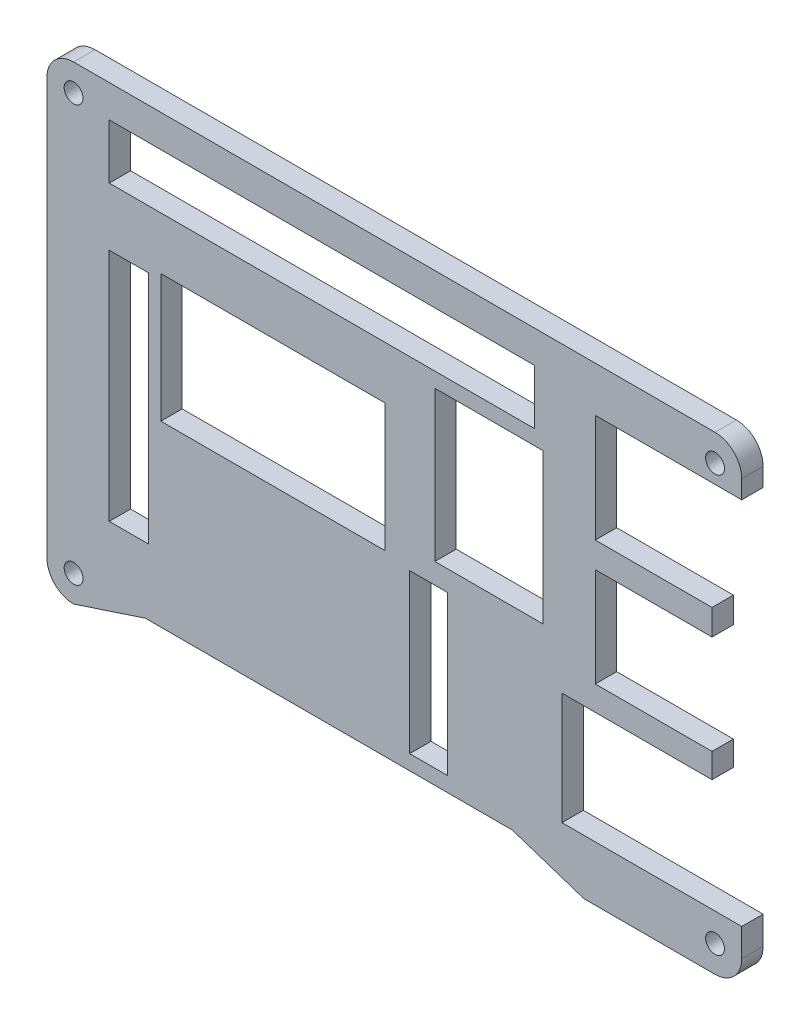
SolidWorks part; units mm, degrees
ref_plane "Front Plane" through (0, 0, 0) normal (0, 0, 1) x (1, 0, 0)
ref_plane "Top Plane" through (0, 0, 0) normal (0, 1, 0) x (1, 0, 0)
ref_plane "Right Plane" through (0, 0, 0) normal (1, 0, 0) x (0, 0, -1)
sketch "Sketch1" plane through (0, 0, 0) normal (0, 0, 1) x (1, 0, 0)
  line L0 (40.325, 24.0683) -> (61.2149, 24.0683) construction
  line L1 (40.325, 8.6582) -> (40.325, 24.0683) construction
  line L2 (56.975, 8.6582) -> (40.325, 8.6582) construction
  line L3 (56.975, 4.9979) -> (56.975, 8.6582) construction
  line L4 (40.325, 4.9979) -> (56.975, 4.9979) construction
  line L5 (40.325, -9.1218) -> (40.325, 4.9979) construction
  line L6 (56.975, -9.1218) -> (40.325, -9.1218) construction
  line L7 (56.975, -12.628) -> (56.975, -9.1218) construction
  line L8 (35.575, -12.628) -> (56.975, -12.628) construction
  line L9 (35.575, -28.6278) -> (35.575, -12.628) construction
  line L10 (61.2149, -28.6278) -> (35.575, -28.6278) construction
  line L11 (61.2149, -32.6134) -> (61.2149, -28.6278) construction
  line L12 (38.7143, -36.451) -> (57.405, -36.451) construction
  line L13 (28.4743, -33.0844) -> (38.7143, -36.451) construction
  line L14 (61.2149, 24.0683) -> (61.2149, 26.6839) construction
  line L15 (40.325, 24.0683) -> (61.2149, 24.0683)
  line L16 (40.325, 8.6582) -> (40.325, 24.0683)
  line L17 (56.975, 8.6582) -> (40.325, 8.6582)
  line L18 (56.975, 4.9979) -> (56.975, 8.6582)
  line L19 (40.325, 4.9979) -> (56.975, 4.9979)
  line L20 (40.325, -9.1218) -> (40.325, 4.9979)
  line L21 (56.975, -9.1218) -> (40.325, -9.1218)
  line L22 (56.975, -12.628) -> (56.975, -9.1218)
  line L23 (35.575, -12.628) -> (56.975, -12.628)
  line L24 (35.575, -28.6278) -> (35.575, -12.628)
  line L25 (61.2149, -28.6278) -> (35.575, -28.6278)
  line L26 (61.2149, -32.6134) -> (61.2149, -28.6278)
  line L27 (38.7143, -36.451) -> (57.405, -36.451)
  line L28 (28.4743, -33.0844) -> (38.7143, -36.451)
  line L29 (61.2149, 24.0683) -> (61.2149, 26.6839)
  line L30 (57.4049, 30.5077) -> (-34.0849, 30.5077) construction
  line L31 (-37.8949, 26.6977) -> (-37.8949, -32.641) construction
  line L32 (-34.0849, -36.451) -> (-23.8449, -33.0844) construction
  line L33 (57.4049, 30.5077) -> (-34.0849, 30.5077)
  line L34 (-37.8949, 26.6977) -> (-37.8949, -32.641)
  line L35 (-34.0849, -36.451) -> (-23.8449, -33.0844)
  line L36 (-23.8449, -33.0844) -> (28.4743, -33.0844)
  line L40 (13.845, -30.9668) -> (13.845, -8.3602)
  line L41 (13.845, -8.3602) -> (19.2484, -8.3602)
  line L42 (19.2484, -8.3602) -> (19.2484, -30.9668)
  line L43 (19.2484, -30.9668) -> (13.845, -30.9668)
  line L45 (-29.0049, 25.897) -> (31.6883, 25.897)
  line L46 (-29.0049, 25.897) -> (-29.0049, 18.087)
  line L47 (-29.0049, 18.087) -> (31.6883, 18.087)
  line L48 (31.6883, 25.897) -> (31.6883, 18.087)
  line L49 (17.441, 15.9724) -> (32.872, 15.9724)
  line L50 (17.441, 15.9724) -> (17.441, -5.4315)
  line L51 (17.441, -5.4315) -> (32.872, -5.4315)
  line L52 (32.872, 15.9724) -> (32.872, -5.4315)
  line L53 (-21.6389, 10.5941) -> (10.329, 10.5941)
  line L54 (-21.6389, 10.5941) -> (-21.6389, -7.643)
  line L55 (-21.6389, -7.643) -> (10.329, -7.643)
  line L56 (10.329, 10.5941) -> (10.329, -7.643)
  line L57 (-23.4169, 9.8012) -> (-29.0049, 9.8012)
  line L58 (-23.4169, 9.8012) -> (-23.4169, -23.6989)
  line L59 (-23.4169, -23.6989) -> (-29.0049, -23.6989)
  line L60 (-29.0049, 9.8012) -> (-29.0049, -23.6989)
  arc A0 (57.405, -36.451) -> (61.2149, -32.6134) centre (57.405, -32.641) ccw construction
  arc A1 (61.2149, 26.6839) -> (57.4049, 30.5077) centre (57.4049, 26.6977) ccw construction
  circle A2 centre (57.4049, 26.6977) radius 1.3462 construction
  circle A3 centre (57.405, -32.641) radius 1.3462 construction
  circle A4 centre (-34.0849, -32.641) radius 1.3462 construction
  circle A5 centre (-34.0849, 26.6977) radius 1.3462 construction
  arc A6 (57.405, -36.451) -> (61.2149, -32.6134) centre (57.405, -32.641) ccw
  arc A7 (61.2149, 26.6839) -> (57.4049, 30.5077) centre (57.4049, 26.6977) ccw
  circle A8 centre (57.4049, 26.6977) radius 1.3462
  circle A9 centre (57.405, -32.641) radius 1.3462
  circle A10 centre (-34.0849, -32.641) radius 1.3462
  circle A11 centre (-34.0849, 26.6977) radius 1.3462
  arc A12 (-34.0849, 30.5077) -> (-37.8949, 26.6977) centre (-34.0849, 26.6977) ccw construction
  arc A13 (-37.8949, -32.641) -> (-34.0849, -36.451) centre (-34.0849, -32.641) ccw construction
  arc A14 (-34.0849, 30.5077) -> (-37.8949, 26.6977) centre (-34.0849, 26.6977) ccw
  arc A15 (-37.8949, -32.641) -> (-34.0849, -36.451) centre (-34.0849, -32.641) ccw
extrude "Boss-Extrude1" add sketch "Sketch1" along normal blind 3.048
